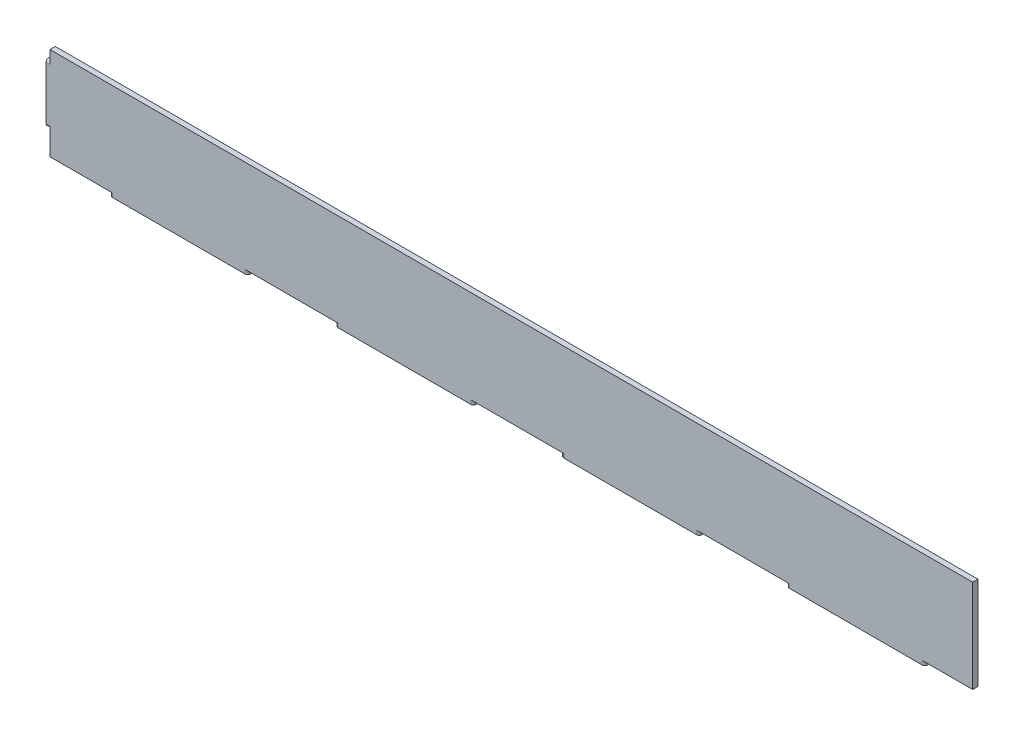
SolidWorks part; units mm, degrees
ref_plane "Front" through (0, 0, 0) normal (0, 0, 1) x (1, 0, 0)
ref_plane "Top" through (0, 0, 0) normal (0, 1, 0) x (1, 0, 0)
ref_plane "Right" through (0, 0, 0) normal (1, 0, 0) x (0, 0, -1)
sketch "Эскиз1" plane through (0, 0, 0) normal (0, 0, 1) x (1, 0, 0)
  line L1 (0, -40.1989) -> (695, -40.1989)
  line L2 (0, -40.1989) -> (0, 29.8011)
  line L3 (0, 29.8011) -> (695, 29.8011)
  line L4 (695, -40.1989) -> (695, 29.8011)
  dimension "D1" = 70
  dimension "D2" = 695
  dimension "D3" = 0
extrude "Бобышка-Вытянуть1" add sketch "Эскиз1" along normal blind 4
sketch "Эскиз2" plane through (0, -40.1989, 0) normal (0, -1, 0) x (1, 0, 0)
  line L0 (47, 2) -> (147, 2) construction
  line L1 (47, 4) -> (147, 4)
  line L2 (47, 0) -> (147, 0)
  line L3 (217, 2) -> (317, 2) construction
  line L4 (217, 4) -> (317, 4)
  line L5 (217, 0) -> (317, 0)
  line L6 (387, 2) -> (487, 2) construction
  line L7 (387, 4) -> (487, 4)
  line L8 (387, 0) -> (487, 0)
  line L9 (557, 2) -> (657, 2) construction
  line L10 (557, 4) -> (657, 4)
  line L11 (557, 0) -> (657, 0)
  arc A0 (47, 4) -> (47, 0) centre (47, 2) ccw
  arc A1 (147, 0) -> (147, 4) centre (147, 2) ccw
  arc A2 (217, 4) -> (217, 0) centre (217, 2) ccw
  arc A3 (317, 0) -> (317, 4) centre (317, 2) ccw
  arc A4 (387, 4) -> (387, 0) centre (387, 2) ccw
  arc A5 (487, 0) -> (487, 4) centre (487, 2) ccw
  arc A6 (557, 4) -> (557, 0) centre (557, 2) ccw
  arc A7 (657, 0) -> (657, 4) centre (657, 2) ccw
  point P4 (97, 2)
  point P12 (267, 2)
  point P19 (437, 2)
  point P26 (607, 2)
  dimension "D1" = 2
  dimension "D2" = 4
extrude "Бобышка-Вытянуть2" add sketch "Эскиз2" along normal blind 3
sketch "Эскиз3" plane through (0, 0, 0) normal (-1, 0, 0) x (0, 0, 1)
  line L0 (2, 20) -> (2, -20) construction
  line L1 (4, 20) -> (4, -20)
  line L2 (0, 20) -> (0, -20)
  arc A0 (4, 20) -> (0, 20) centre (2, 20) ccw
  arc A1 (0, -20) -> (4, -20) centre (2, -20) ccw
  point P4 (2, 0)
  dimension "D1" = 2
extrude "Бобышка-Вытянуть3" add sketch "Эскиз3" along normal blind 3
